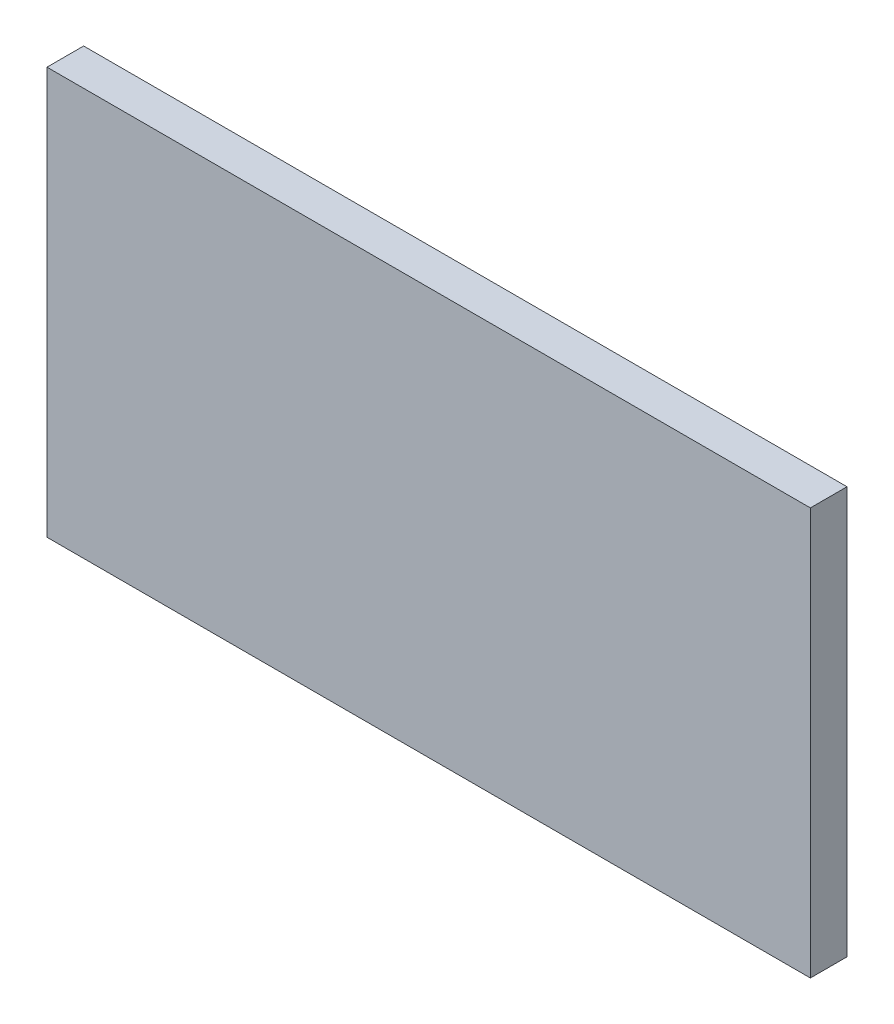
SolidWorks part; units mm, degrees
ref_plane "Alzado" through (0, 0, 0) normal (0, 0, 1) x (1, 0, 0)
ref_plane "Planta" through (0, 0, 0) normal (0, 1, 0) x (1, 0, 0)
ref_plane "Vista lateral" through (0, 0, 0) normal (1, 0, 0) x (0, 0, -1)
ref_plane "Plano_ParedChicaSur" through (0, 50, 0) normal (0, 1, 0) x (1, 0, 0)
sketch "SkParedChicaSur" plane through (0, 50, 0) normal (0, 1, 0) x (1, 0, 0)
  line L1 (-187.5, 187.5) -> (187.5, 187.5)
  line L2 (-187.5, 187.5) -> (-187.5, 205.5)
  line L3 (-187.5, 205.5) -> (187.5, 205.5)
  line L4 (187.5, 187.5) -> (187.5, 205.5)
extrude "ParedChicaSur" add sketch "SkParedChicaSur" along normal blind 200 separate body
